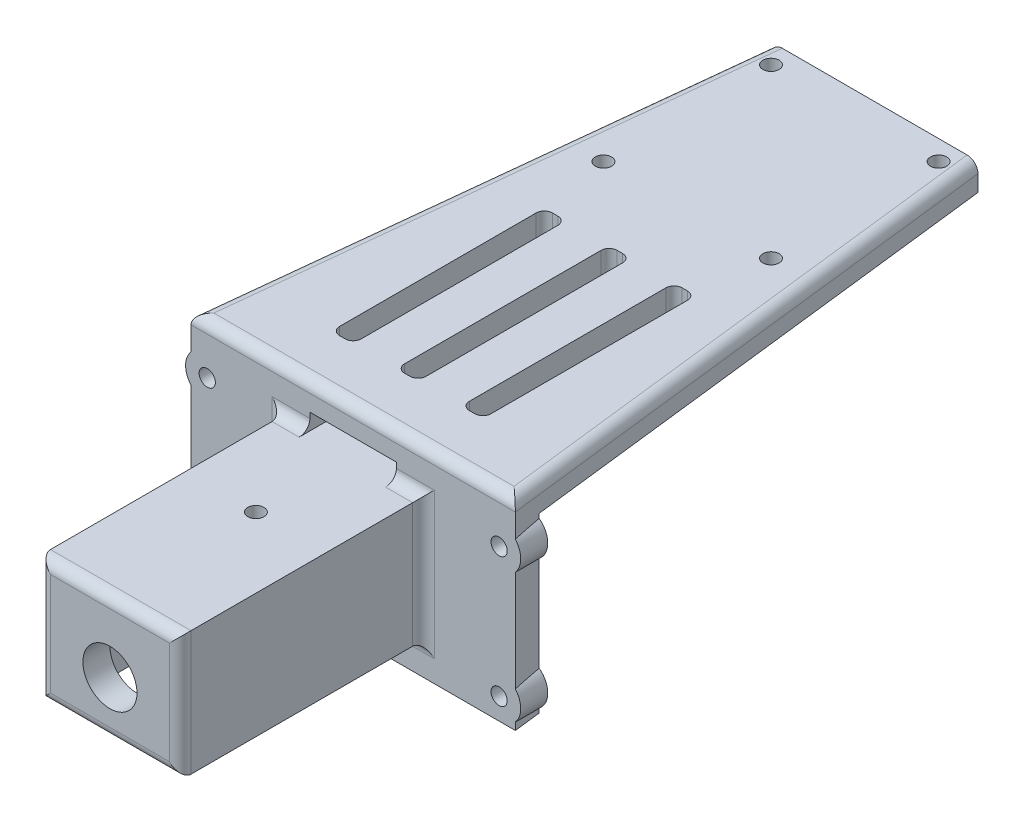
SolidWorks part; units mm, degrees
ref_plane "Front Plane" through (0, 0, 0) normal (0, 0, 1) x (1, 0, 0)
ref_plane "Top Plane" through (0, 0, 0) normal (0, 1, 0) x (1, 0, 0)
ref_plane "Right Plane" through (0, 0, 0) normal (1, 0, 0) x (0, 0, -1)
sketch "Sketch1" plane through (0, 0, 0) normal (0, 0, 1) x (1, 0, 0)
  line L1 (30, -16) -> (-30, -16)
  line L2 (30, -16) -> (30, 16)
  line L3 (30, 16) -> (-30, 16)
  line L4 (-30, -16) -> (-30, 16)
  line L5 (30, -16) -> (-30, 16) construction
  line L6 (30, 16) -> (-30, -16) construction
  point P0 (0, 0)
  dimension "D1" = 32
  dimension "D2" = 60
extrude "Boss-Extrude1" add sketch "Sketch1" along normal blind 5
sketch "Sketch2" plane through (0, 0, 5) normal (0, 0, 1) x (1, 0, 0)
  line L0 (30, 16) -> (-30, 16) construction
  line L1 (-30, -16) -> (30, -16) construction
  line L2 (30, -16) -> (30, 16) construction
  line L3 (-30, 16) -> (-30, -16) construction
  circle A0 centre (27, 12) radius 1.5
  circle A1 centre (27, -12) radius 1.5
  circle A2 centre (-27, -12) radius 1.5
  circle A3 centre (-27, 12) radius 1.5
  dimension "D9" = 3
  dimension "D10" = 3
  dimension "D11" = 3
  dimension "D12" = 3
  dimension "D1" = 4
  dimension "D2" = 4
  dimension "D3" = 4
  dimension "D4" = 4
  dimension "D5" = 3
  dimension "D6" = 3
  dimension "D7" = 3
  dimension "D8" = 3
extrude "Cut-Extrude1" cut sketch "Sketch2" against normal blind 5
sketch "Sketch3" plane through (0, 0, 5) normal (0, 0, 1) x (1, 0, 0)
  line L0 (-30, 16) -> (30, -16) construction
  line L1 (30, -16) -> (30, 16) construction
  line L2 (30, 16) -> (-30, -16) construction
sketch "Sketch4" plane through (0, 0, 5) normal (0, 0, 1) x (1, 0, 0)
  circle A0 centre (0, 0) radius 5
  dimension "D1" = 10
extrude "Cut-Extrude2" cut sketch "Sketch4" against normal blind 5
sketch "Sketch5" plane through (0, 0, 5) normal (0, 0, 1) x (1, 0, 0)
  line L1 (-30, 16) -> (30, 16)
  line L2 (-30, 16) -> (-30, 21)
  line L3 (-30, 21) -> (30, 21)
  line L4 (30, 16) -> (30, 21)
  dimension "D1" = 5
extrude "Boss-Extrude2" add sketch "Sketch5" against normal blind 97
sketch "Sketch6" plane through (0, 16, 0) normal (0, -1, 0) x (1, 0, 0)
  line L0 (30, -92) -> (30, 0) construction
  line L1 (-16, -88.3) -> (15, -88.3)
  line L2 (-16, -88.3) -> (-16, -57.3)
  line L3 (-16, -57.3) -> (15, -57.3)
  line L4 (15, -88.3) -> (15, -57.3)
  line L7 (-30, -92) -> (30, -92) construction
  circle A0 centre (15, -57.3) radius 1.5
  circle A1 centre (-16, -57.3) radius 1.5
  circle A2 centre (15, -88.3) radius 1.5
  circle A3 centre (-16, -88.3) radius 1.5
  dimension "D5" = 3
  dimension "D6" = 3
  dimension "D7" = 3
  dimension "D8" = 3
  dimension "D1" = 31
  dimension "D2" = 31
  dimension "D3" = 15
  dimension "D4" = 3.7
extrude "Cut-Extrude3" cut sketch "Sketch6" against normal blind 100 contours A0 | A1 | A2 | A3
sketch "Sketch7" plane through (0, 21, 0) normal (0, 1, 0) x (1, 0, 0)
  line L0 (30, -5) -> (18.5924, 92)
  line L1 (30, 92) -> (-30, 92) construction
  line L2 (-30, -5) -> (-19.6271, 92)
  line L3 (-19.6271, 92) -> (-30, 92)
  line L4 (-30, 92) -> (-30, -5)
  line L5 (18.5924, 92) -> (30, 92)
  line L6 (30, 92) -> (30, -5)
  point P7 (15, 88.3)
  point P8 (-16, 88.3)
  dimension "D1" = 4
  dimension "D2" = 4
extrude "Cut-Extrude4" cut sketch "Sketch7" against normal blind 100
sketch "Sketch8" plane through (0, 0, 5) normal (0, 0, 1) x (1, 0, 0)
  line L0 (13, 13) -> (-13, 13)
  line L2 (10, -10) -> (10, 10)
  line L3 (10, 10) -> (-10, 10)
  line L4 (-10, -10) -> (-10, 10)
  line L5 (10, -10) -> (-10, 10) construction
  line L6 (10, 10) -> (-10, -10) construction
  line L7 (-13, -10) -> (-13, 13)
  line L9 (13, -10) -> (13, 13)
  line L10 (13, -13) -> (-13, -13) construction
  line L11 (10, -10) -> (-10, -10) construction
  line L12 (13, -10) -> (10, -10)
  line L13 (13, -13) -> (13, 13) construction
  line L14 (-13, -13) -> (-13, 13) construction
  line L15 (-10, -10) -> (-13, -10)
  point P0 (0, 0)
  dimension "D2" = 20
  dimension "D3" = 3
extrude "Boss-Extrude3" add sketch "Sketch8" along normal blind 45
sketch "Sketch9" plane through (0, 0, 50) normal (0, 0, 1) x (1, 0, 0)
  line L0 (-13, -10) -> (13, -10)
  line L2 (-13, -10) -> (-13, 13)
  line L3 (-13, 13) -> (13, 13)
  line L4 (13, -10) -> (13, 13)
  line L5 (-10, -10) -> (13, 13) construction
  line L6 (-13, 13) -> (10, -10) construction
  point P0 (0, 0)
extrude "Boss-Extrude4" add sketch "Sketch9" against normal blind 5
sketch "Sketch10" plane through (0, 0, 50) normal (0, 0, 1) x (1, 0, 0)
  circle A0 centre (0, 0) radius 5
  dimension "D1" = 10
extrude "Cut-Extrude5" cut sketch "Sketch10" against normal blind 5
sketch "Sketch17" plane through (0, 0, 5) normal (0, 0, 1) x (1, 0, 0)
  line L0 (13, 13) -> (-13, 13) construction
  line L1 (8, 13) -> (-8, 13)
  line L2 (8, 13) -> (8, 16)
  line L3 (8, 16) -> (-8, 16)
  line L4 (-8, 13) -> (-8, 16)
  line L5 (-13, 13) -> (-13, -10) construction
  dimension "D1" = 16
  dimension "D2" = 3
  dimension "D3" = 5
extrude "Cut-Extrude6" cut sketch "Sketch17" against normal blind 10
sketch "Sketch18" plane through (0, 13, 0) normal (0, 1, 0) x (1, 0, 0)
  line L0 (13, -50) -> (-13, -50) construction
  line L2 (-13, -50) -> (-13, -5) construction
  circle A0 centre (0, -23) radius 1.5
  dimension "D1" = 3
  dimension "D2" = 27
  dimension "D3" = 13
extrude "Cut-Extrude7" cut sketch "Sketch18" against normal blind 10
fillet "Fillet3" radius 2 3 edges at (-24.8136, 21, -43.5) (24.2962, 21, -43.5) (0, 21, 5)
fillet "Fillet4" radius 2 4 edges at (0, -10, 50) (13, 1.5, 50) (-13, 1.5, 50) (0, 13, 50)
fillet "Fillet5" radius 2 6 edges at (10.5, 13, 5) (-10.5, 13, 5) (-11.5, -10, 5) (11.5, -10, 5) (13, 1.5, 5) (-13, 1.5, 5)
sketch "Sketch34" plane through (0, 0, 5) normal (0, 0, 1) x (1, 0, 0)
  circle A0 centre (-27, 12) radius 1.5
  circle A1 centre (-27, 12) radius 4
  dimension "D1" = 8
  dimension "D2" = 3
extrude "Boss-Extrude5" add sketch "Sketch34" against normal blind 5
sketch "Sketch36" plane through (0, 0, 5) normal (0, 0, 1) x (1, 0, 0)
  circle A0 centre (-27, -12) radius 1.5
  circle A1 centre (-27, -12) radius 4
  dimension "D1" = 3
  dimension "D2" = 8
extrude "Boss-Extrude6" add sketch "Sketch36" against normal blind 5
sketch "Sketch37" plane through (0, 0, 5) normal (0, 0, 1) x (1, 0, 0)
  circle A0 centre (27, 12) radius 1.5
  circle A1 centre (27, 12) radius 4
  dimension "D1" = 3
  dimension "D2" = 8
extrude "Boss-Extrude7" add sketch "Sketch37" against normal blind 5
sketch "Sketch38" plane through (0, 0, 5) normal (0, 0, 1) x (1, 0, 0)
  circle A0 centre (27, -12) radius 1.5
  circle A1 centre (27, -12) radius 4
  dimension "D1" = 3
  dimension "D2" = 8
extrude "Boss-Extrude8" add sketch "Sketch38" against normal blind 5
sketch "Sketch40" plane through (0, 21, 0) normal (0, 1, 0) x (1, 0, 0)
  line L0 (0, 5) -> (0, 44.3482)
  line L1 (12, 5) -> (12, 44.3482)
  line L2 (-12, 5) -> (-12, 44.3482)
  line L3 (30, -5) -> (-30, -5) construction
  line L4 (14, 5) -> (14, 44.3482)
  line L5 (10, 5) -> (10, 44.3482)
  line L6 (2, 5) -> (2, 44.3482)
  line L7 (-10, 5) -> (-10, 44.3482)
  line L8 (-2, 5) -> (-2, 44.3482)
  line L9 (-14, 5) -> (-14, 44.3482)
  line L10 (-14, 44.3482) -> (-10, 44.3482)
  line L11 (-2, 44.3482) -> (2, 44.3482)
  line L12 (10, 44.3482) -> (14, 44.3482)
  line L13 (14, 5) -> (10, 5)
  line L15 (-10, 5) -> (-14, 5)
  line L16 (-15, -5) -> (-8, -5) construction
  line L17 (-2, 5) -> (2, 5)
  line L18 (2, 0) -> (2, 44.3482) construction
  line L19 (0, 0) -> (0, 44.3482) construction
  line L20 (-2, 0) -> (-2, 44.3482) construction
  dimension "D1" = 12
  dimension "D2" = 12
  dimension "D3" = 10
  dimension "D8" = 10
  dimension "D4" = 2
  dimension "D5" = 2
  dimension "D6" = 2
  dimension "D7" = 2
extrude "Cut-Extrude8" cut sketch "Sketch40" against normal blind 10 contours L9 L10 L7 L15 | L8 L11 L6 L17 | L5 L12 L4 L13
fillet "Fillet6" radius 1.5 12 edges at (-10, 18.5, -5) (2, 18.5, -5) (14, 18.5, -5) (10, 18.5, -5) (-2, 18.5, -5) (-14, 18.5, -5) (-10, 18.5, -44.3482) (2, 18.5, -44.3482) (14, 18.5, -44.3482) (-14, 18.5, -44.3482) (-2, 18.5, -44.3482) (10, 18.5, -44.3482)
sketch "Sketch43" plane through (-13, 0, 0) normal (-1, 0, 0) x (0, 0, 1)
  line L0 (48, -10) -> (48, 13) construction
  line L1 (48, 13) -> (7, 13) construction
  circle A0 centre (40, 1.5) radius 1.5
  dimension "D1" = 3
  dimension "D2" = 8
  dimension "D3" = 11.5
extrude "Cut-Extrude10" cut sketch "Sketch43" against normal blind 9
